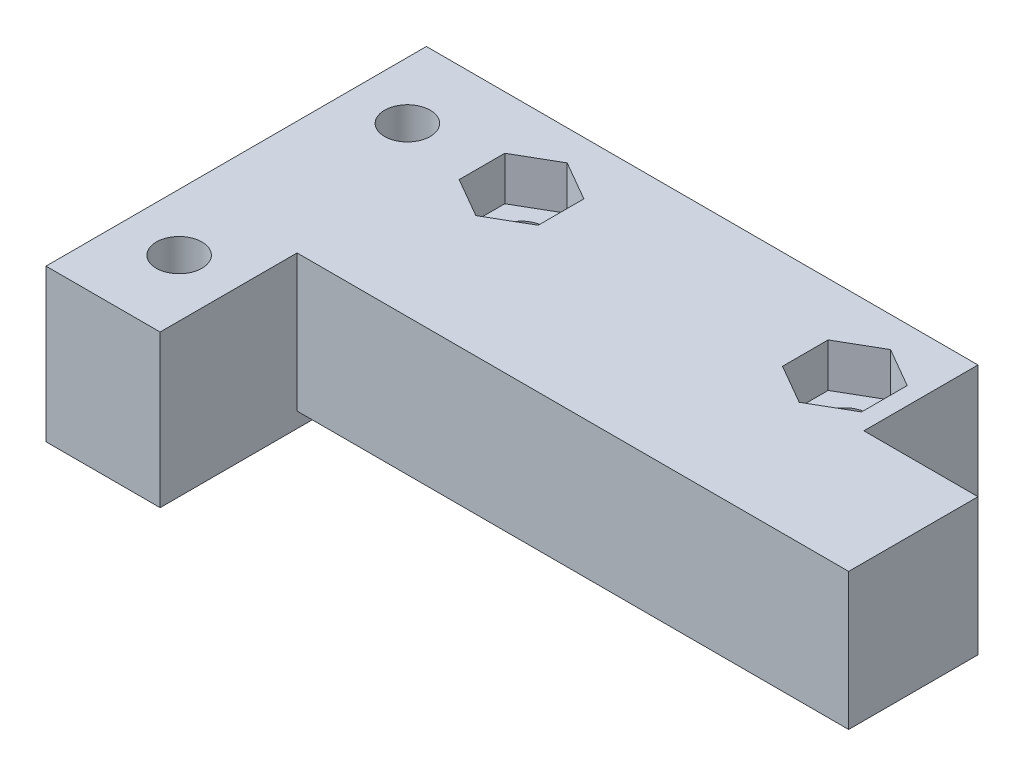
SolidWorks part; units mm, degrees
ref_plane "前基準面" through (0, 0, 0) normal (0, 0, 1) x (1, 0, 0)
ref_plane "上基準面" through (0, 0, 0) normal (0, 1, 0) x (1, 0, 0)
ref_plane "右基準面" through (0, 0, 0) normal (1, 0, 0) x (0, 0, -1)
sketch "草圖1" plane through (0, 0, 0) normal (0, 1, 0) x (1, 0, 0)
  line L1 (0, 0) -> (35, 0)
  line L2 (0, 0) -> (0, 20)
  line L3 (0, 20) -> (35, 20)
  line L4 (35, 0) -> (35, 20)
  dimension "D1" = 35
  dimension "D2" = 20
extrude "填料-伸長1" add sketch "草圖1" along normal blind 8
sketch "草圖2" plane through (0, 0, 0) normal (0, 1, 0) x (1, 0, 0)
  line L0 (0, 20) -> (0, 0) construction
  line L1 (6, 0) -> (35, 0)
  line L2 (6, 0) -> (6, 14)
  line L3 (6, 14) -> (35, 14)
  line L4 (35, 0) -> (35, 14)
  dimension "D1" = 29
  dimension "D2" = 14
  dimension "D3" = 6
  dimension "D4" = 14
extrude "除料-伸長2" cut sketch "草圖2" along normal blind 0.8
sketch "草圖3" plane through (0, 0, 0) normal (0, 1, 0) x (1, 0, 0)
  line L1 (6, 0) -> (35, 0)
  line L2 (6, 0) -> (6, 7.2)
  line L3 (6, 7.2) -> (35, 7.2)
  line L4 (35, 0) -> (35, 7.2)
  dimension "D1" = 29
  dimension "D2" = 7.2
extrude "除料-伸長4" cut sketch "草圖3" along normal through all
sketch "草圖4" plane through (0, 0, 0) normal (0, 1, 0) x (1, 0, 0)
  line L1 (35, 20) -> (29, 20)
  line L2 (35, 20) -> (35, 14)
  line L3 (35, 14) -> (29, 14)
  line L4 (29, 20) -> (29, 14)
  dimension "D1" = 6
  dimension "D2" = 6
extrude "除料-伸長5" cut sketch "草圖4" along normal through all
sketch "草圖5" plane through (0, 0, 0) normal (0, 1, 0) x (1, 0, 0)
  circle A0 centre (3, 16) radius 1.2
  circle A1 centre (3, 4) radius 1.2
  circle A2 centre (9, 16) radius 1.2
  circle A4 centre (26, 16) radius 1.2
extrude "除料-伸長6" cut sketch "草圖5" along normal through all
sketch "草圖7" plane through (0, 0, 0) normal (0, 1, 0) x (1, 0, 0)
  line L1 (26, 18.4) -> (23.9215, 17.2)
  line L2 (23.9215, 17.2) -> (23.9215, 14.8)
  line L3 (23.9215, 14.8) -> (26, 13.6)
  line L4 (26, 13.6) -> (28.0785, 14.8)
  line L5 (28.0785, 14.8) -> (28.0785, 17.2)
  line L6 (28.0785, 17.2) -> (26, 18.4)
  line L8 (9, 18.4) -> (6.9215, 17.2)
  line L9 (6.9215, 17.2) -> (6.9215, 14.8)
  line L10 (6.9215, 14.8) -> (9, 13.6)
  line L11 (9, 13.6) -> (11.0785, 14.8)
  line L12 (11.0785, 14.8) -> (11.0785, 17.2)
  line L13 (11.0785, 17.2) -> (9, 18.4)
  circle A0 centre (9, 16) radius 2.0785 construction
  circle A1 centre (26, 16) radius 2.0785 construction
  dimension "D1" = 4.8
  dimension "D2" = 4.8
extrude "除料-伸長8" cut sketch "草圖7" against normal blind 2.3 from surface at 8 starting at face at (9, 8, -14.8)
sketch "草圖6" plane through (0, 0, 0) normal (0, 1, 0) x (1, 0, 0)
  circle A1 centre (3, 16) radius 2.2
  circle A2 centre (3, 4) radius 2.2
extrude "除料-伸長10" cut sketch "草圖6" along normal blind 2 from surface at 0 starting at face at (9, 0, -14.8)
